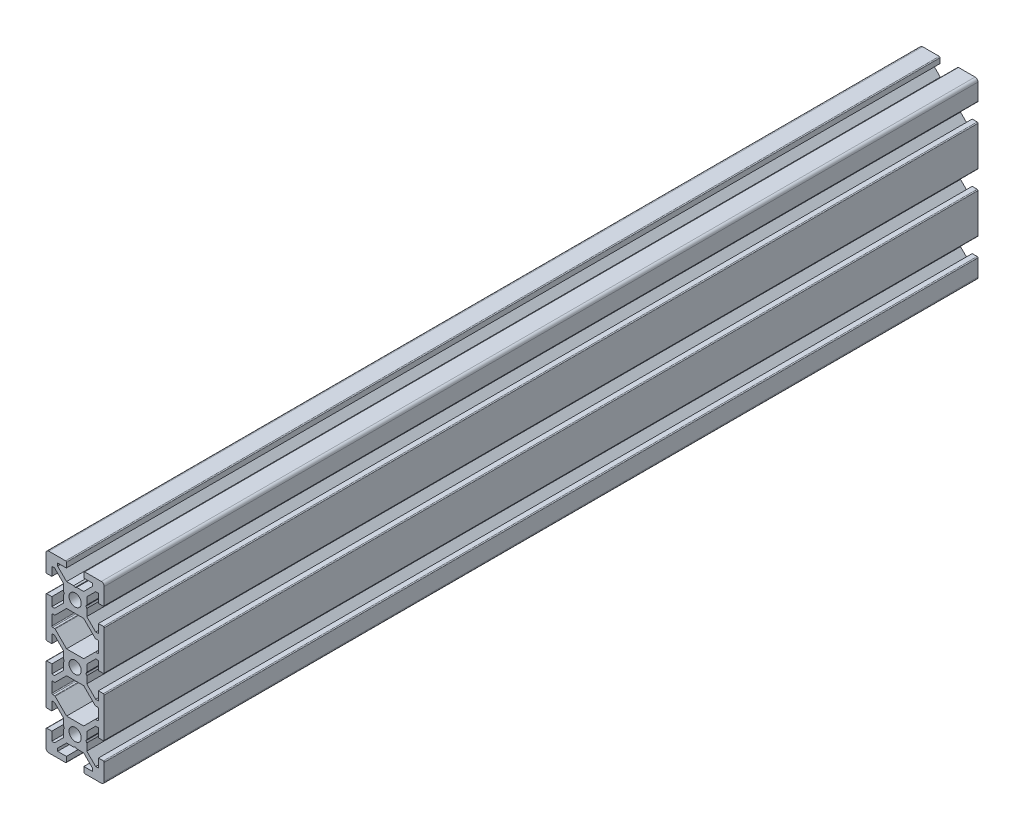
SolidWorks part; units mm, degrees
ref_plane "Front Plane" through (0, 0, 0) normal (0, 0, 1) x (1, 0, 0)
ref_plane "Top Plane" through (0, 0, 0) normal (0, 1, 0) x (1, 0, 0)
ref_plane "Right Plane" through (0, 0, 0) normal (1, 0, 0) x (0, 0, -1)
ref_plane "Plane1" through (0, 0, 0) normal (0, 0, 1) x (1, 0, 0)
sketch "Sketch1" plane through (0, 0, 0) normal (0, 0, 1) x (1, 0, 0)
  line L0 (-10, 16.7) -> (-10, 3.3)
  line L1 (-9.7, 3) -> (-8, 3)
  line L2 (-8, 3) -> (-8, 6)
  line L3 (-8, 6) -> (-7.0607, 6)
  line L4 (-7.0607, 6) -> (-4, 2.9393)
  line L5 (-4, 2.9393) -> (-4, 0.5196)
  line L6 (-4, 0.5196) -> (-3.7, 0)
  line L7 (-3.7, 0) -> (-4, -0.5196)
  line L8 (-4, -0.5196) -> (-4, -2.9394)
  line L9 (-4, -2.9394) -> (-7.0606, -6)
  line L10 (-7.0606, -6) -> (-8, -6)
  line L11 (-8, -6) -> (-8, -3)
  line L12 (-8, -3) -> (-9.7, -3)
  line L13 (-10, -3.3) -> (-10, -16.7)
  line L14 (-9.7, -17) -> (-8, -17)
  line L15 (-8, -17) -> (-8, -14)
  line L16 (-8, -14) -> (-7.0607, -14)
  line L17 (-7.0607, -14) -> (-4, -17.0607)
  line L18 (-4, -17.0607) -> (-4, -19.4804)
  line L19 (-4, -19.4804) -> (-3.7, -20)
  line L20 (-3.7, -20) -> (-4, -20.5196)
  line L21 (-4, -20.5196) -> (-4, -22.9394)
  line L22 (-4, -22.9394) -> (-7.0606, -26)
  line L23 (-7.0606, -26) -> (-8, -26)
  line L24 (-8, -26) -> (-8, -23)
  line L25 (-8, -23) -> (-9.7, -23)
  line L26 (-10, -23.3) -> (-10, -29)
  line L27 (-9, -30) -> (-3.3, -30)
  line L28 (-3, -29.7) -> (-3, -28)
  line L29 (-3, -28) -> (-6, -28)
  line L30 (-6, -28) -> (-6, -27.0607)
  line L31 (-6, -27.0607) -> (-2.9393, -24)
  line L32 (-2.9393, -24) -> (-0.5191, -24)
  line L33 (-0.5191, -24) -> (0, -23.7)
  line L34 (0, -23.7) -> (0.5186, -24)
  line L35 (0.5186, -24) -> (2.9393, -24)
  line L36 (2.9393, -24) -> (6, -27.0607)
  line L37 (6, -27.0607) -> (6, -28)
  line L38 (6, -28) -> (3, -28)
  line L39 (3, -28) -> (3, -29.7)
  line L40 (3.3, -30) -> (9, -30)
  line L41 (10, -29) -> (10, -23.3)
  line L42 (9.7, -23) -> (8, -23)
  line L43 (8, -23) -> (8, -26)
  line L44 (8, -26) -> (7.0606, -26)
  line L45 (7.0606, -26) -> (4, -22.9394)
  line L46 (4, -22.9394) -> (4, -20.5196)
  line L47 (4, -20.5196) -> (3.7, -20)
  line L48 (3.7, -20) -> (4, -19.4804)
  line L49 (4, -19.4804) -> (4, -17.0607)
  line L50 (4, -17.0607) -> (7.0607, -14)
  line L51 (7.0607, -14) -> (8, -14)
  line L52 (8, -14) -> (8, -17)
  line L53 (8, -17) -> (9.7, -17)
  line L54 (10, -16.7) -> (10, -3.3)
  line L55 (9.7, -3) -> (8, -3)
  line L56 (8, -3) -> (8, -6)
  line L57 (8, -6) -> (7.0607, -6)
  line L58 (7.0607, -6) -> (4, -2.9393)
  line L59 (4, -2.9393) -> (4, -0.5196)
  line L60 (4, -0.5196) -> (3.7, 0)
  line L61 (3.7, 0) -> (4, 0.5196)
  line L62 (4, 0.5196) -> (4, 2.9393)
  line L63 (4, 2.9393) -> (7.0607, 6)
  line L64 (7.0607, 6) -> (8, 6)
  line L65 (8, 6) -> (8, 3)
  line L66 (8, 3) -> (9.7, 3)
  line L67 (10, 3.3) -> (10, 16.7)
  line L68 (9.7, 17) -> (8, 17)
  line L69 (8, 17) -> (8, 14)
  line L70 (8, 14) -> (7.0607, 14)
  line L71 (7.0607, 14) -> (4, 17.0607)
  line L72 (4, 17.0607) -> (4, 19.4804)
  line L73 (4, 19.4804) -> (3.7, 20)
  line L74 (3.7, 20) -> (4, 20.5196)
  line L75 (4, 20.5196) -> (4, 22.9394)
  line L76 (4, 22.9394) -> (7.0606, 26)
  line L77 (7.0606, 26) -> (8, 26)
  line L78 (8, 26) -> (8, 23)
  line L79 (8, 23) -> (9.7, 23)
  line L80 (10, 23.3) -> (10, 29)
  line L81 (9, 30) -> (3.3, 30)
  line L82 (3, 29.7) -> (3, 28)
  line L83 (3, 28) -> (6, 28)
  line L84 (6, 28) -> (6, 27.0607)
  line L85 (6, 27.0607) -> (2.9393, 24)
  line L86 (2.9393, 24) -> (0.5196, 24)
  line L87 (0.5196, 24) -> (0, 23.7)
  line L88 (0, 23.7) -> (-0.5196, 24)
  line L89 (-0.5196, 24) -> (-2.9393, 24)
  line L90 (-2.9393, 24) -> (-6, 27.0607)
  line L91 (-6, 27.0607) -> (-6, 28)
  line L92 (-6, 28) -> (-3, 28)
  line L93 (-3, 28) -> (-3, 29.7)
  line L94 (-3.3, 30) -> (-9, 30)
  line L95 (-10, 29) -> (-10, 23.3)
  line L96 (-9.7, 23) -> (-8, 23)
  line L97 (-8, 23) -> (-8, 26)
  line L98 (-8, 26) -> (-7.0606, 26)
  line L99 (-7.0606, 26) -> (-4, 22.9394)
  line L100 (-4, 22.9394) -> (-4, 20.5196)
  line L101 (-4, 20.5196) -> (-3.7, 20)
  line L102 (-3.7, 20) -> (-4, 19.4804)
  line L103 (-4, 19.4804) -> (-4, 17.0607)
  line L104 (-4, 17.0607) -> (-7.0607, 14)
  line L105 (-7.0607, 14) -> (-8, 14)
  line L106 (-8, 14) -> (-8, 17)
  line L107 (-8, 17) -> (-9.7, 17)
  line L108 (-7.7, 8) -> (-7.0636, 8)
  line L109 (-6.8515, 7.9121) -> (-2.9393, 4)
  line L110 (-2.9393, 4) -> (2.9393, 4)
  line L111 (2.9393, 4) -> (6.8515, 7.9121)
  line L112 (7.0636, 8) -> (7.7, 8)
  line L113 (8, 8.3) -> (8, 11.7)
  line L114 (7.7, 12) -> (7.0636, 12)
  line L115 (6.8515, 12.0879) -> (2.9393, 16)
  line L116 (2.9393, 16) -> (-2.9393, 16)
  line L117 (-2.9393, 16) -> (-6.8515, 12.0879)
  line L118 (-7.0636, 12) -> (-7.7, 12)
  line L119 (-8, 11.7) -> (-8, 8.3)
  line L120 (-8, -8.3) -> (-8, -11.7)
  line L121 (-7.7, -12) -> (-7.0636, -12)
  line L122 (-6.8515, -12.0879) -> (-2.9394, -16)
  line L123 (-2.9394, -16) -> (2.9393, -16)
  line L124 (2.9393, -16) -> (6.8515, -12.0879)
  line L125 (7.0636, -12) -> (7.7, -12)
  line L126 (8, -11.7) -> (8, -8.3)
  line L127 (7.7, -8) -> (7.0636, -8)
  line L128 (6.8515, -7.9121) -> (2.9393, -4)
  line L129 (2.9393, -4) -> (-2.9393, -4)
  line L130 (-2.9393, -4) -> (-6.8515, -7.9121)
  line L131 (-7.0636, -8) -> (-7.7, -8)
  arc A0 (-10, 3.3) -> (-9.7, 3) centre (-9.7, 3.3) ccw
  arc A1 (-9.7, -3) -> (-10, -3.3) centre (-9.7, -3.3) ccw
  arc A2 (-10, -16.7) -> (-9.7, -17) centre (-9.7, -16.7) ccw
  arc A3 (-9.7, -23) -> (-10, -23.3) centre (-9.7, -23.3) ccw
  arc A4 (-10, -29) -> (-9, -30) centre (-9, -29) ccw
  arc A5 (-3.3, -30) -> (-3, -29.7) centre (-3.3, -29.7) ccw
  arc A6 (3, -29.7) -> (3.3, -30) centre (3.3, -29.7) ccw
  arc A7 (9, -30) -> (10, -29) centre (9, -29) ccw
  arc A8 (10, -23.3) -> (9.7, -23) centre (9.7, -23.3) ccw
  arc A9 (9.7, -17) -> (10, -16.7) centre (9.7, -16.7) ccw
  arc A10 (10, -3.3) -> (9.7, -3) centre (9.7, -3.3) ccw
  arc A11 (9.7, 3) -> (10, 3.3) centre (9.7, 3.3) ccw
  arc A12 (10, 16.7) -> (9.7, 17) centre (9.7, 16.7) ccw
  arc A13 (9.7, 23) -> (10, 23.3) centre (9.7, 23.3) ccw
  arc A14 (10, 29) -> (9, 30) centre (9, 29) ccw
  arc A15 (3.3, 30) -> (3, 29.7) centre (3.3, 29.7) ccw
  arc A16 (-3, 29.7) -> (-3.3, 30) centre (-3.3, 29.7) ccw
  arc A17 (-9, 30) -> (-10, 29) centre (-9, 29) ccw
  arc A18 (-10, 23.3) -> (-9.7, 23) centre (-9.7, 23.3) ccw
  arc A19 (-9.7, 17) -> (-10, 16.7) centre (-9.7, 16.7) ccw
  circle A20 centre (0, 20) radius 2.1
  circle A21 centre (0, 0) radius 2.1
  circle A22 centre (0, -20) radius 2.1
  arc A23 (-8, 8.3) -> (-7.7, 8) centre (-7.7, 8.3) ccw
  arc A24 (-7.0636, 8) -> (-6.8515, 7.9121) centre (-7.0636, 7.7) cw
  arc A25 (6.8515, 7.9121) -> (7.0636, 8) centre (7.0636, 7.7) cw
  arc A26 (7.7, 8) -> (8, 8.3) centre (7.7, 8.3) ccw
  arc A27 (8, 11.7) -> (7.7, 12) centre (7.7, 11.7) ccw
  arc A28 (7.0636, 12) -> (6.8515, 12.0879) centre (7.0636, 12.3) cw
  arc A29 (-6.8515, 12.0879) -> (-7.0636, 12) centre (-7.0636, 12.3) cw
  arc A30 (-7.7, 12) -> (-8, 11.7) centre (-7.7, 11.7) ccw
  arc A31 (-8, -11.7) -> (-7.7, -12) centre (-7.7, -11.7) ccw
  arc A32 (-7.0636, -12) -> (-6.8515, -12.0879) centre (-7.0636, -12.3) cw
  arc A33 (6.8515, -12.0879) -> (7.0636, -12) centre (7.0636, -12.3) cw
  arc A34 (7.7, -12) -> (8, -11.7) centre (7.7, -11.7) ccw
  arc A35 (8, -8.3) -> (7.7, -8) centre (7.7, -8.3) ccw
  arc A36 (7.0636, -8) -> (6.8515, -7.9121) centre (7.0636, -7.7) cw
  arc A37 (-6.8515, -7.9121) -> (-7.0636, -8) centre (-7.0636, -7.7) cw
  arc A38 (-7.7, -8) -> (-8, -8.3) centre (-7.7, -8.3) ccw
extrude "Boss-Extrude1" add sketch "Sketch1" against normal blind 300
